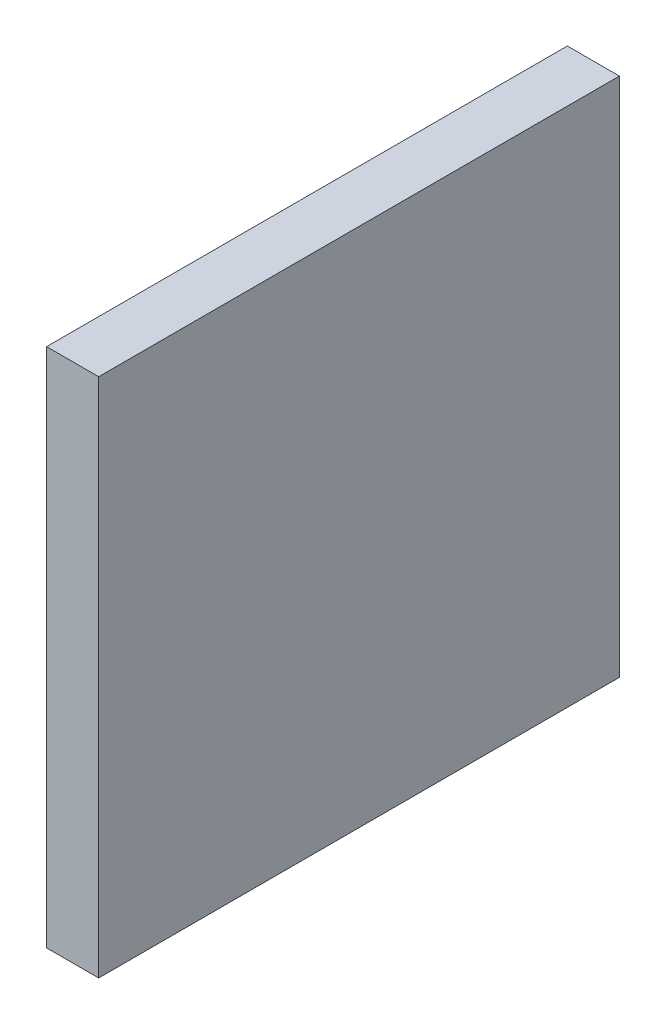
SolidWorks part; units mm, degrees
ref_plane "Front Plane" through (0, 0, 0) normal (0, 0, 1) x (1, 0, 0)
ref_plane "Top Plane" through (0, 0, 0) normal (0, 1, 0) x (1, 0, 0)
ref_plane "Right Plane" through (0, 0, 0) normal (1, 0, 0) x (0, 0, -1)
sketch "Sketch1" plane through (0, 0, 0) normal (0, 1, 0) x (1, 0, 0)
  line L1 (50, -500) -> (-50, -500)
  line L2 (50, -500) -> (50, 500)
  line L3 (50, 500) -> (-50, 500)
  line L4 (-50, -500) -> (-50, 500)
  line L5 (50, -500) -> (-50, 500) construction
  line L6 (50, 500) -> (-50, -500) construction
  point P0 (0, 0)
  dimension "D1" = 100
  dimension "D2" = 1000
extrude "Boss-Extrude1" add sketch "Sketch1" along normal blind 1000
